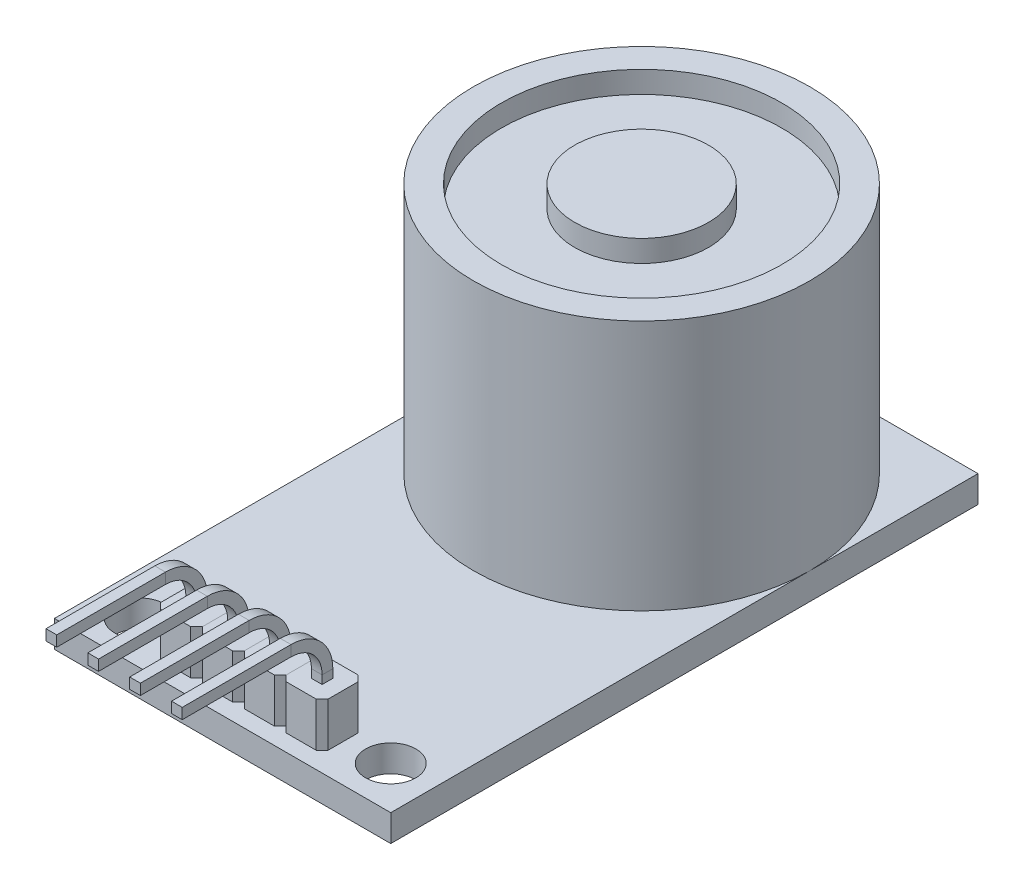
SolidWorks part; units mm, degrees
ref_plane "Front Plane" through (0, 0, 0) normal (0, 0, 1) x (1, 0, 0)
ref_plane "Top Plane" through (0, 0, 0) normal (0, 1, 0) x (1, 0, 0)
ref_plane "Right Plane" through (0, 0, 0) normal (1, 0, 0) x (0, 0, -1)
sketch "Sketch1" plane through (0, 0, 0) normal (0, 1, 0) x (1, 0, 0)
  line L1 (-10.05, 17.545) -> (10.05, 17.545)
  line L2 (-10.05, 17.545) -> (-10.05, -17.545)
  line L3 (-10.05, -17.545) -> (10.05, -17.545)
  line L4 (10.05, 17.545) -> (10.05, -17.545)
  line L5 (-10.05, 17.545) -> (10.05, -17.545) construction
  line L6 (-10.05, -17.545) -> (10.05, 17.545) construction
  point P0 (0, 0)
  dimension "D1" = 35.09
  dimension "D2" = 20.1
extrude "Boss-Extrude1" add sketch "Sketch1" along normal blind 1.6
sketch "Sketch2" plane through (0, 1.6, 0) normal (0, 1, 0) x (1, 0, 0)
  line L0 (10.05, -17.545) -> (10.05, 17.545) construction
  line L1 (10.05, 17.545) -> (-10.05, 17.545) construction
  line L2 (-10.05, 17.545) -> (-10.05, -17.545) construction
  circle A0 centre (0, 7.495) radius 10.05
extrude "Boss-Extrude2" add sketch "Sketch2" along normal blind 15
sketch "Sketch3" plane through (0, 1.6, 0) normal (0, 1, 0) x (1, 0, 0)
  line L0 (-4.6964, -14.045) -> (-2.9036, -14.045)
  line L4 (-2.9036, -14.045) -> (-2.55, -14.3986)
  line L10 (-4.6964, -14.045) -> (-5.05, -14.3986)
  line L11 (-4.6965, -16.545) -> (-5.05, -16.1914)
  line L12 (-5.05, -16.1914) -> (-5.05, -14.3986)
  line L16 (-2.55, -14.3986) -> (-2.55, -16.1914)
  line L17 (-10.05, -17.545) -> (10.05, -17.545) construction
  line L19 (-10.05, 7.495) -> (-10.05, -17.545) construction
  line L27 (-2.9036, -16.545) -> (-2.55, -16.1914)
  line L31 (-4.6965, -16.545) -> (-2.9036, -16.545)
  dimension "D1" = 2.5
  dimension "D2" = 2.5
  dimension "D3" = 1
  dimension "D4" = 5
  dimension "D5" = 135
  dimension "D6" = 0.5
extrude "Boss-Extrude3" add sketch "Sketch3" along normal blind 2.65
sketch "Sketch4" plane through (0, 4.25, 0) normal (0, 1, 0) x (1, 0, 0)
  line L0 (-4.6965, -16.545) -> (-2.9036, -16.545) construction
  line L5 (-4.12, -14.975) -> (-3.48, -14.975)
  line L6 (-4.12, -14.975) -> (-4.12, -15.615)
  line L7 (-4.12, -15.615) -> (-3.48, -15.615)
  line L8 (-3.48, -14.975) -> (-3.48, -15.615)
  line L9 (-4.12, -14.975) -> (-3.48, -15.615) construction
  line L10 (-4.12, -15.615) -> (-3.48, -14.975) construction
  line L11 (-5.05, -14.3986) -> (-5.05, -16.1914) construction
  point P0 (-3.8, -15.295)
  point P8 (-3.8, -16.545)
  point P12 (-5.05, -15.295)
  dimension "D1" = 0.64
ref_plane "Plane2" through (-3.8, 0, 0) normal (-1, 0, 0) x (0, 0, 1)
sketch "Sketch58" plane through (-3.8, 0, 0) normal (-1, 0, 0) x (0, 0, 1)
  line L0 (17.475, 7.25) -> (23.975, 7.25)
  line L1 (14.975, 4.75) -> (14.975, 4.25)
  arc A0 (14.975, 4.75) -> (17.475, 7.25) centre (17.475, 4.75) cw
  dimension "D1" = 2.5
  dimension "D2" = 6.5
  dimension "D3" = 0.5
sweep "Sweep1" add profiles "Sketch4" path "Sketch58"
pattern_linear "LPattern1" count 4 spacing 2.5 along (1, 0, 0) of "Boss-Extrude3", "Sweep1"
sketch "Sketch59" plane through (0, 1.6, 0) normal (0, 1, 0) x (1, 0, 0)
  line L0 (7.5, -14.995) -> (-7.5, -14.995) construction
  line L1 (-10.05, -17.545) -> (10.05, -17.545) construction
  circle A0 centre (-7.5, -14.995) radius 1.5
  circle A1 centre (7.5, -14.995) radius 1.5
  point P6 (0, -14.995)
  point P8 (0, -17.545)
  dimension "D1" = 3
  dimension "D2" = 15
  dimension "D3" = 2.55
extrude "Cut-Extrude1" cut sketch "Sketch59" against normal through all
sketch "Sketch60" plane through (0, 16.6, 0) normal (0, 1, 0) x (1, 0, 0)
  circle A0 centre (0, 7.495) radius 4
  circle A1 centre (0, 7.495) radius 8.375
  dimension "D1" = 8
  dimension "D2" = 16.75
extrude "Cut-Extrude2" cut sketch "Sketch60" against normal blind 1.3
